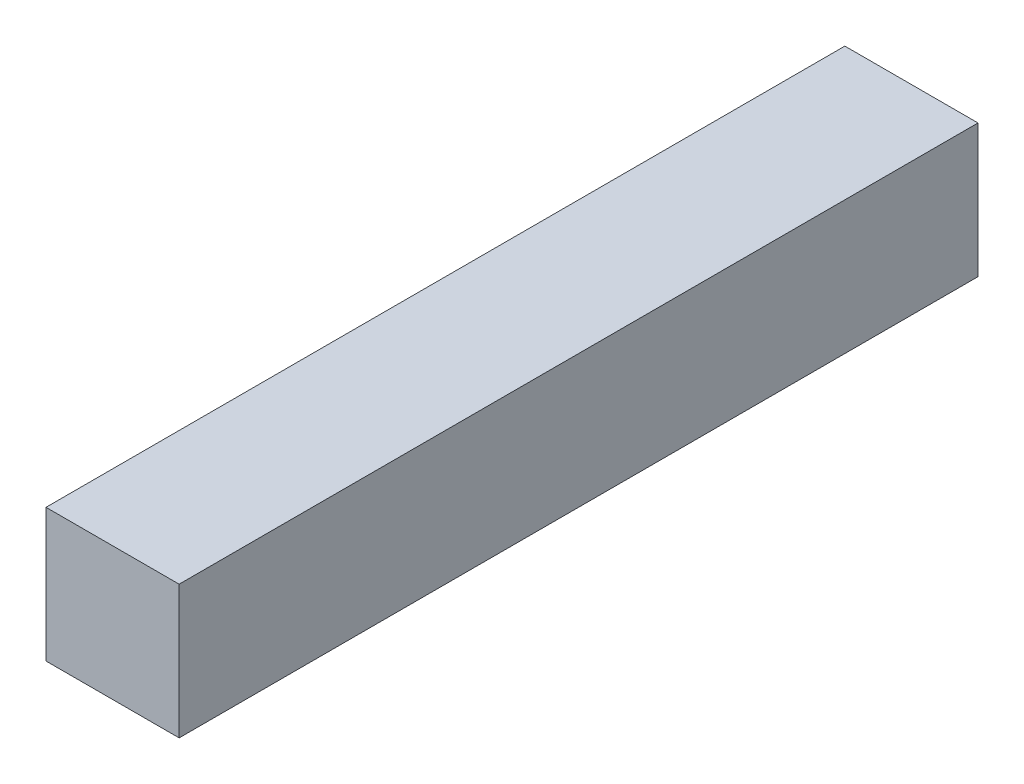
SolidWorks part; units mm, degrees
ref_plane "Front Plane" through (0, 0, 0) normal (0, 0, 1) x (1, 0, 0)
ref_plane "Top Plane" through (0, 0, 0) normal (0, 1, 0) x (1, 0, 0)
ref_plane "Right Plane" through (0, 0, 0) normal (1, 0, 0) x (0, 0, -1)
sketch "Sketch1" plane through (0, 0, 0) normal (0, 0, 1) x (1, 0, 0)
  line L1 (12.7, -12.7) -> (-12.7, -12.7)
  line L2 (12.7, -12.7) -> (12.7, 12.7)
  line L3 (12.7, 12.7) -> (-12.7, 12.7)
  line L4 (-12.7, -12.7) -> (-12.7, 12.7)
  line L5 (12.7, -12.7) -> (-12.7, 12.7) construction
  line L6 (12.7, 12.7) -> (-12.7, -12.7) construction
  point P0 (0, 0)
  dimension "D1" = 25.4
extrude "Boss-Extrude1" add sketch "Sketch1" along normal blind 152.4
